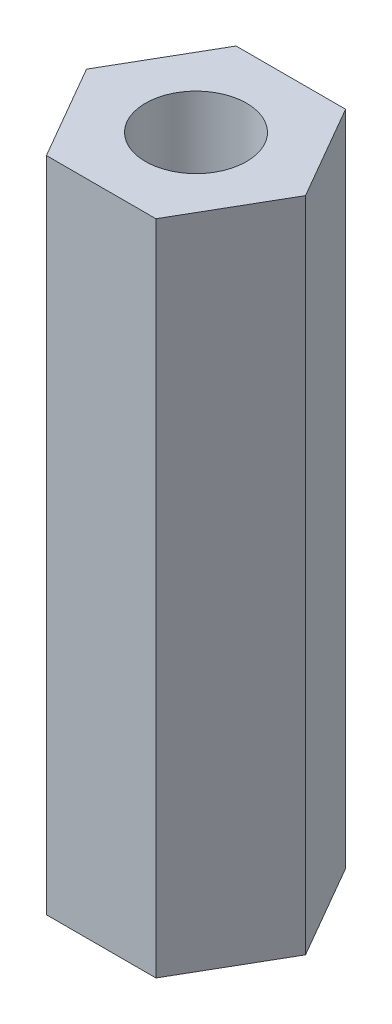
SolidWorks part; units mm, degrees
ref_plane "Front Plane" through (0, 0, 0) normal (0, 0, 1) x (1, 0, 0)
ref_plane "Top Plane" through (0, 0, 0) normal (0, 1, 0) x (1, 0, 0)
ref_plane "Right Plane" through (0, 0, 0) normal (1, 0, 0) x (0, 0, -1)
sketch "Sketch1" plane through (0, 0, 0) normal (0, 1, 0) x (1, 0, 0)
  line L1 (2.1651, 3.75) -> (-2.1651, 3.75)
  line L2 (-2.1651, 3.75) -> (-4.3301, 0)
  line L3 (-4.3301, 0) -> (-2.1651, -3.75)
  line L4 (-2.1651, -3.75) -> (2.1651, -3.75)
  line L5 (2.1651, -3.75) -> (4.3301, 0)
  line L6 (4.3301, 0) -> (2.1651, 3.75)
  circle A0 centre (0, 0) radius 3.75 construction
  circle A1 centre (0, 0) radius 2
  dimension "D1" = 7.5
  dimension "D2" = 4
extrude "Boss-Extrude1" add sketch "Sketch1" along normal blind 26
